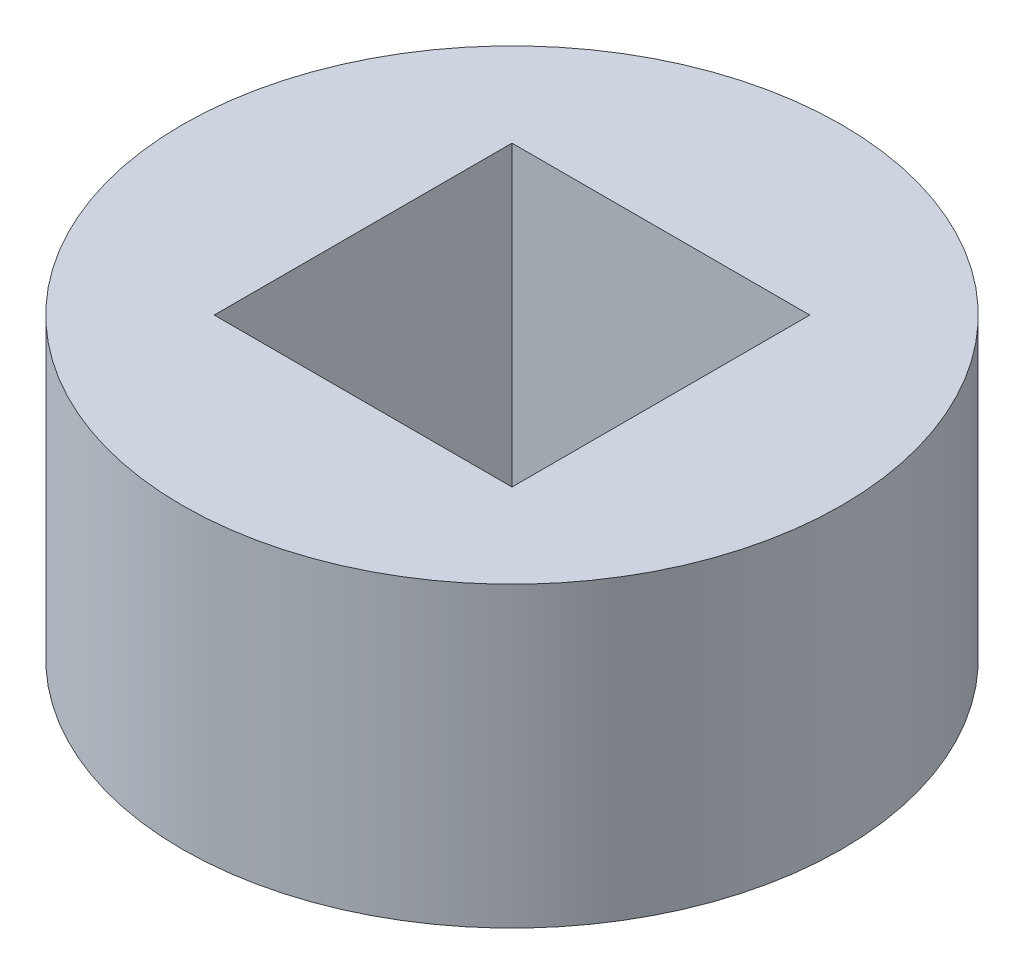
SolidWorks part; units mm, degrees
ref_plane "Front Plane" through (0, 0, 0) normal (0, 0, 1) x (1, 0, 0)
ref_plane "Top Plane" through (0, 0, 0) normal (0, 1, 0) x (1, 0, 0)
ref_plane "Right Plane" through (0, 0, 0) normal (1, 0, 0) x (0, 0, -1)
sketch "Elevator Axle Bearing" plane through (0, 0, 0) normal (0, 1, 0) x (1, 0, 0)
  line L1 (-3.175, 3.175) -> (3.175, 3.175)
  line L2 (-3.175, 3.175) -> (-3.175, -3.175)
  line L3 (-3.175, -3.175) -> (3.175, -3.175)
  line L4 (3.175, 3.175) -> (3.175, -3.175)
  line L5 (-3.175, 3.175) -> (3.175, -3.175) construction
  line L6 (-3.175, -3.175) -> (3.175, 3.175) construction
  circle A0 centre (0, 0) radius 7.0301
  dimension "D1" = 14.0603
  dimension "D2" = 6.35
  dimension "D3" = 6.35
extrude "Boss-Extrude1" add sketch "Elevator Axle Bearing" along normal blind 6.35
equation "\"Ball Diameter\"= 1.75in"
equation "\"Sheet Thickness\"= 0.25in"
equation "\"Screw Diameter\"= .17in"
equation "\"Robot Diameter\"= 14in"
equation "\"Castor Screw Diameter\"= 0.22in"
equation "\"Wheel Diameter\" = 4in"
equation "\"Nut Diameter\" = 8.4mm"
equation "\"Nut Height\" = 2.9mm"
equation "\"Screw Height\" = 0.55in"
equation "\"Pulley Diameter\" = 1in"
equation "\"Reactor Height\" = 14in"
equation "\"Elevator Height\" = 11.5in"
equation "\"Elevator Width\" = \"Ball Diameter\" + 0.25in"
equation "\"Elevator Bearing Diameter\" = sqr(2*(\"Sheet Thickness\"^2)) + 0.2in"
equation "\"Elevator Axle Length\" = \"Elevator Width\" + 8*\"Sheet Thickness\""
equation "\"D1@Elevator Axle Bearing\"=\"Elevator Bearing Diameter\""
equation "\"D2@Elevator Axle Bearing\"=\"Sheet Thickness\""
equation "\"D3@Elevator Axle Bearing\"=\"Sheet Thickness\""
equation "\"D1@Boss-Extrude1\"=\"Sheet Thickness\""
